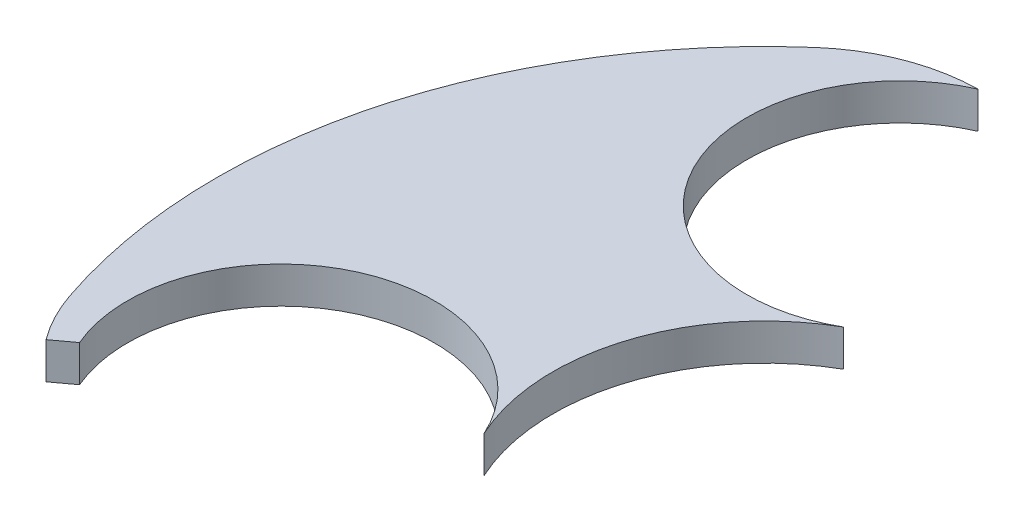
SolidWorks part; units mm, degrees
ref_plane "Plan de face" through (0, 0, 0) normal (0, 0, 1) x (1, 0, 0)
ref_plane "Plan de dessus" through (0, 0, 0) normal (0, 1, 0) x (1, 0, 0)
ref_plane "Plan de droite" through (0, 0, 0) normal (1, 0, 0) x (0, 0, -1)
sketch "Esquisse1" plane through (0, 0, 0) normal (0, 1, 0) x (1, 0, 0)
  line L0 (-84.4585, -44.8337) -> (-81.8158, -42.8843)
  line L3 (-9.4508, 5.6286) -> (-14.9085, -3.5351) construction
  line L5 (3.3105, -15.9387) -> (9.4508, -5.6286) construction
  line L12 (0, 0) -> (-80, 0) construction
  line L13 (-64.3402, -29.9927) -> (-49.9731, 23.6261) construction
  line L14 (-65, 0) -> (-64.3402, -29.9927) construction
  arc A0 (-43.3841, -25.9503) -> (3.3105, -15.9387) centre (-29.8877, 25) ccw construction
  arc A1 (-19.8222, -3.882) -> (-14.9085, -3.5351) centre (-17.486, -2) ccw construction
  arc A2 (-19.8222, -3.882) -> (-31.3986, 11.2169) centre (288.4615, 244.468) cw construction
  arc A3 (-14.9569, 14.9816) -> (-23.7434, -42.1488) centre (-16.9847, -13.9474) ccw
  arc A36 (-49.9731, 23.6261) -> (-64.3402, -29.9927) centre (-16.9847, -13.9474) ccw construction
  arc A37 (-66.4673, 42.4128) -> (-88.018, -38.0154) centre (-16.9847, -13.9474) ccw
  arc A40 (-88.018, -38.0154) -> (-84.4585, -44.8337) centre (-64.3402, -29.9927) ccw
  arc A41 (9.4508, -5.6286) -> (-9.4508, 5.6286) centre (0, 0) ccw construction
  arc A42 (-17.0622, 36.0526) -> (-48.1141, -53.0749) centre (-16.9847, -13.9474) ccw construction
  arc A43 (-50.3798, 48.6228) -> (-31.3986, 11.2169) centre (-41.8363, 29.4392) ccw
  arc A44 (-50.3798, 48.6228) -> (-66.4673, 42.4128) centre (-49.9731, 23.6261) ccw
  arc A45 (-43.3841, -25.9503) -> (-81.8158, -42.8843) centre (-62.5009, -34.6421) ccw
  point P78 (-56.6847, 2.6915)
  point P85 (-65, 0)
  dimension "D4" = 25
  dimension "D5" = 12
  dimension "D6" = 21
  dimension "D7" = 25
  dimension "D8" = 25
  dimension "D10" = 3
  dimension "D11" = 17.6
  dimension "D18" = 80
  dimension "D20" = 75
  dimension "D26" = 11
  dimension "D13" = 50
  dimension "D14" = 21
  dimension "D12" = 2
  dimension "D22" = 30
  dimension "D23" = 75
  dimension "D24" = 28
  dimension "D25" = 15
  dimension "D30" = 10
  dimension "D32" = 5
extrude "Boss.-Extru.1" add sketch "Esquisse1" along normal blind 5 contours A45 A3 A43 A44 A37 A40 L0
